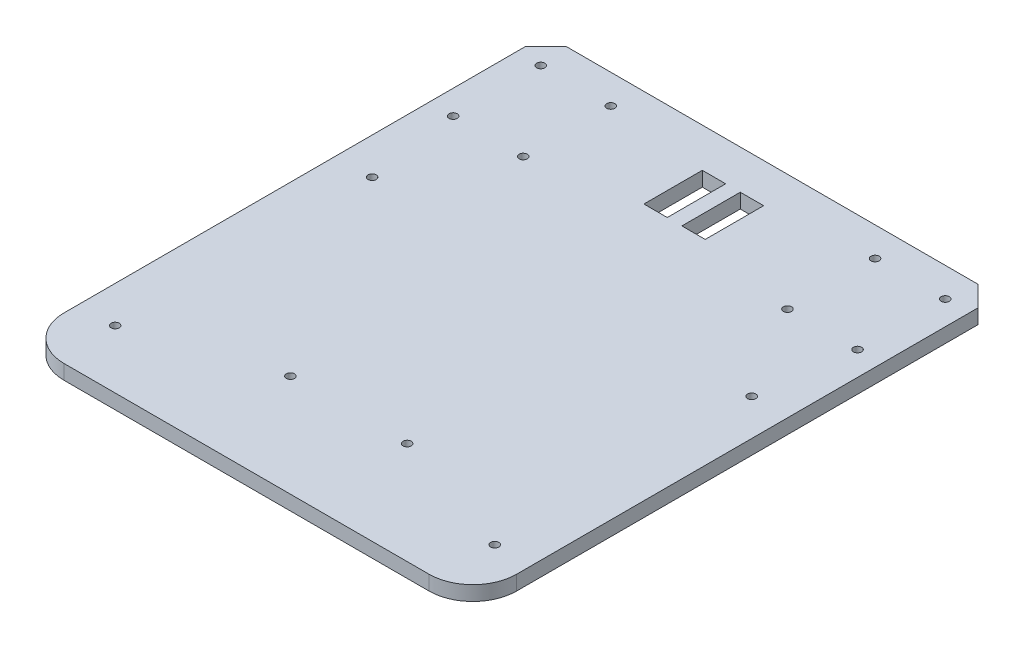
SolidWorks part; units mm, degrees
ref_plane "Front Plane" through (0, 0, 0) normal (0, 0, 1) x (1, 0, 0)
ref_plane "Top Plane" through (0, 0, 0) normal (0, 1, 0) x (1, 0, 0)
ref_plane "Right Plane" through (0, 0, 0) normal (1, 0, 0) x (0, 0, -1)
sketch "Sketch7" plane through (0, 0, 0) normal (0, 1, 0) x (1, 0, 0)
  line L1 (77.5, -90) -> (-77.5, -90)
  line L2 (77.5, -90) -> (77.5, 90)
  line L3 (77.5, 90) -> (-77.5, 90)
  line L4 (-77.5, -90) -> (-77.5, 90)
  line L5 (77.5, -90) -> (-77.5, 90) construction
  line L6 (77.5, 90) -> (-77.5, -90) construction
  point P0 (0, 0)
  dimension "D1" = 155
  dimension "D2" = 180
extrude "Boss-Extrude2" add sketch "Sketch7" along normal blind 5
sketch "Sketch8" plane through (0, 5, 0) normal (0, 1, 0) x (1, 0, 0)
  line L0 (-77.5, 90) -> (-77.5, -90) construction
  line L1 (77.5, 90) -> (-77.5, 90) construction
  circle A0 centre (-69.25, 80) radius 1.4
  circle A1 centre (-69.25, 50) radius 1.4
  circle A2 centre (-45.25, 50) radius 1.4
  circle A3 centre (-45.25, 80) radius 1.4
  circle A4 centre (45.25, 80) radius 1.4
  circle A5 centre (45.25, 50) radius 1.4
  circle A6 centre (69.25, 50) radius 1.4
  circle A7 centre (69.25, 80) radius 1.4
  dimension "D1" = 8.25
  dimension "D3" = 30
  dimension "D2" = 10
  dimension "D4" = 8.25
  dimension "D5" = 24
  dimension "D6" = 40
  dimension "D7" = 10
  dimension "D8" = 24
extrude "Cut-Extrude3" cut sketch "Sketch8" against normal blind 5
sketch "Sketch9" plane through (0, 5, 0) normal (0, 1, 0) x (1, 0, 0)
  line L4 (-77.5, 90) -> (-77.5, -90) construction
  circle A0 centre (-65, 18) radius 1.4
  circle A1 centre (65, 18) radius 1.4
  circle A2 centre (-65, -70) radius 1.4
  circle A3 centre (65, -70) radius 1.4
  dimension "D1" = 88
  dimension "D2" = 88
  dimension "D3" = 12.5
  dimension "D4" = 130
  dimension "D5" = 130
extrude "Cut-Extrude4" cut sketch "Sketch9" against normal blind 5
sketch "Sketch10" plane through (0, 5, 0) normal (0, 1, 0) x (1, 0, 0)
  line L0 (-77.5, -90) -> (-62.5, -90)
  line L1 (-77.5, -90) -> (77.5, -90) construction
  line L2 (-77.5, -90) -> (-77.5, -75)
  line L3 (-77.5, 90) -> (-77.5, -90) construction
  line L6 (77.5, -90) -> (77.5, -75)
  line L7 (77.5, -90) -> (62.5, -90)
  arc A0 (-62.5, -90) -> (-77.5, -75) centre (-62.5, -75) cw
  arc A1 (62.5, -90) -> (77.5, -75) centre (62.5, -75) ccw
  dimension "D1" = 15
  dimension "D2" = 15
extrude "Cut-Extrude5" cut sketch "Sketch10" against normal blind 5
sketch "Sketch11" plane through (0, 5, 0) normal (0, 1, 0) x (1, 0, 0)
  line L1 (-2.5, 56.5855) -> (-10.5, 76.5855) construction
  line L2 (-2.5, 76.5855) -> (-10.5, 56.5855) construction
  line L4 (2.5, 76.5855) -> (10.5, 76.5855)
  line L5 (2.5, 76.5855) -> (2.5, 56.5855)
  line L6 (2.5, 56.5855) -> (10.5, 56.5855)
  line L7 (10.5, 76.5855) -> (10.5, 56.5855)
  line L8 (2.5, 76.5855) -> (10.5, 56.5855) construction
  line L9 (2.5, 56.5855) -> (10.5, 76.5855) construction
  line L11 (-10.5, 76.5855) -> (-10.5, 56.5855)
  line L12 (-2.5, 56.5855) -> (-10.5, 56.5855)
  line L13 (-2.5, 76.5855) -> (-2.5, 56.5855)
  line L14 (-2.5, 76.5855) -> (-10.5, 76.5855)
  point P6 (6.5, 66.5855)
  point P16 (-6.5, 66.5855)
  dimension "D1" = 8
  dimension "D2" = 20
extrude "Cut-Extrude6" cut sketch "Sketch11" against normal blind 5
sketch "Sketch13" plane through (0, 5, 0) normal (0, 1, 0) x (1, 0, 0)
  line L0 (-70.5, 90) -> (-77.5, 83)
  line L1 (77.5, 90) -> (-77.5, 90) construction
  line L2 (-77.5, 90) -> (-77.5, -75) construction
  line L3 (-77.5, 83) -> (-77.5, 90)
  line L4 (-77.5, 90) -> (-70.5, 90)
  line L5 (70.5, 90) -> (77.5, 83)
  line L6 (77.5, 83) -> (77.5, 90)
  line L7 (77.5, 90) -> (70.5, 90)
  dimension "D1" = 7
  dimension "D2" = 7
extrude "Cut-Extrude7" cut sketch "Sketch13" against normal blind 5
sketch "Sketch15" plane through (0, 5, 0) normal (0, 1, 0) x (1, 0, 0)
  line L2 (-62.5, -90) -> (62.5, -90) construction
  circle A0 centre (-20, -55) radius 1.4
  circle A1 centre (20, -55) radius 1.4
  dimension "D2" = 35
extrude "Cut-Extrude8" cut sketch "Sketch15" against normal blind 10
